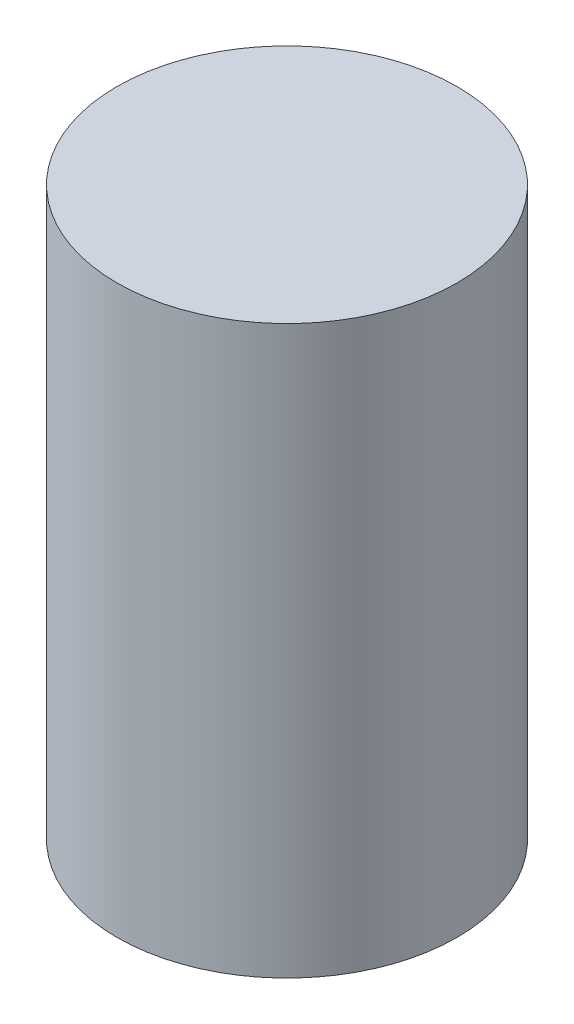
SolidWorks part; units mm, degrees
ref_plane "Front Plane" through (0, 0, 0) normal (0, 0, 1) x (1, 0, 0)
ref_plane "Top Plane" through (0, 0, 0) normal (0, 1, 0) x (1, 0, 0)
ref_plane "Right Plane" through (0, 0, 0) normal (1, 0, 0) x (0, 0, -1)
other "Configuration Table"
sketch "Sketch1" plane through (0, 0, 0) normal (0, 1, 0) x (1, 0, 0)
  circle A0 centre (180, 200) radius 60
extrude "STORE_sog1_kompresor" add sketch "Sketch1" along normal blind 200 from offset 1680 separate body
